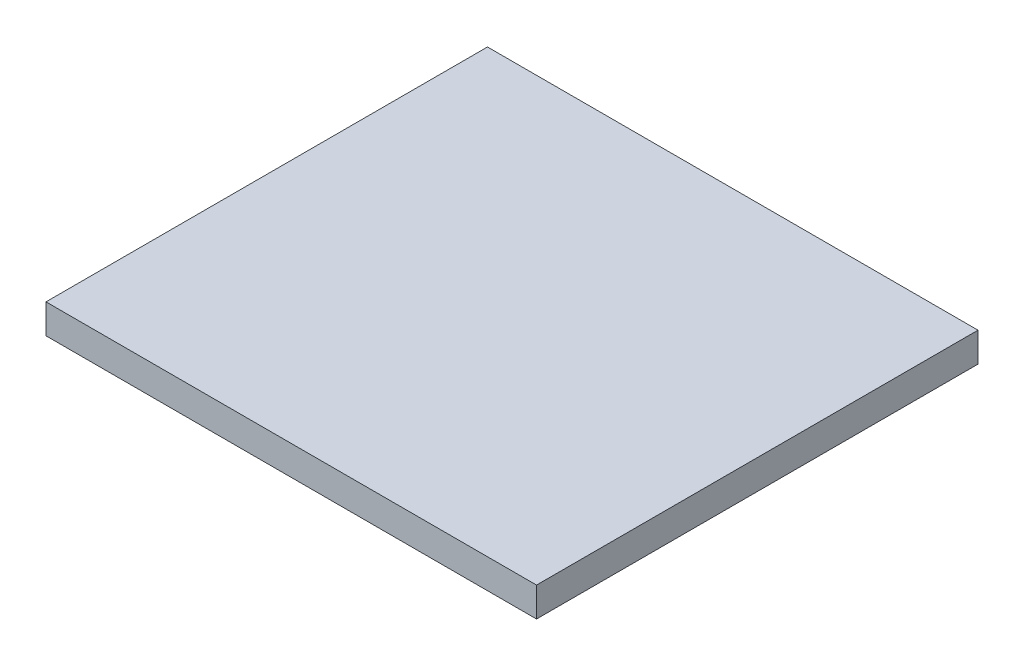
SolidWorks part; units mm, degrees
material "Concreto"
ref_plane "Alzado" through (0, 0, 0) normal (0, 0, 1) x (1, 0, 0)
ref_plane "Planta" through (0, 0, 0) normal (0, 1, 0) x (1, 0, 0)
ref_plane "Vista lateral" through (0, 0, 0) normal (1, 0, 0) x (0, 0, -1)
sketch "Croquis1" plane through (0, 0, 0) normal (0, 1, 0) x (1, 0, 0)
  line L1 (0, 0) -> (5000, 0)
  line L2 (0, 0) -> (0, 4500)
  line L3 (0, 4500) -> (5000, 4500)
  line L4 (5000, 0) -> (5000, 4500)
  dimension "D1" = 5000
  dimension "D2" = 4500
extrude "Saliente-Extruir1" add sketch "Croquis1" along normal blind 300
